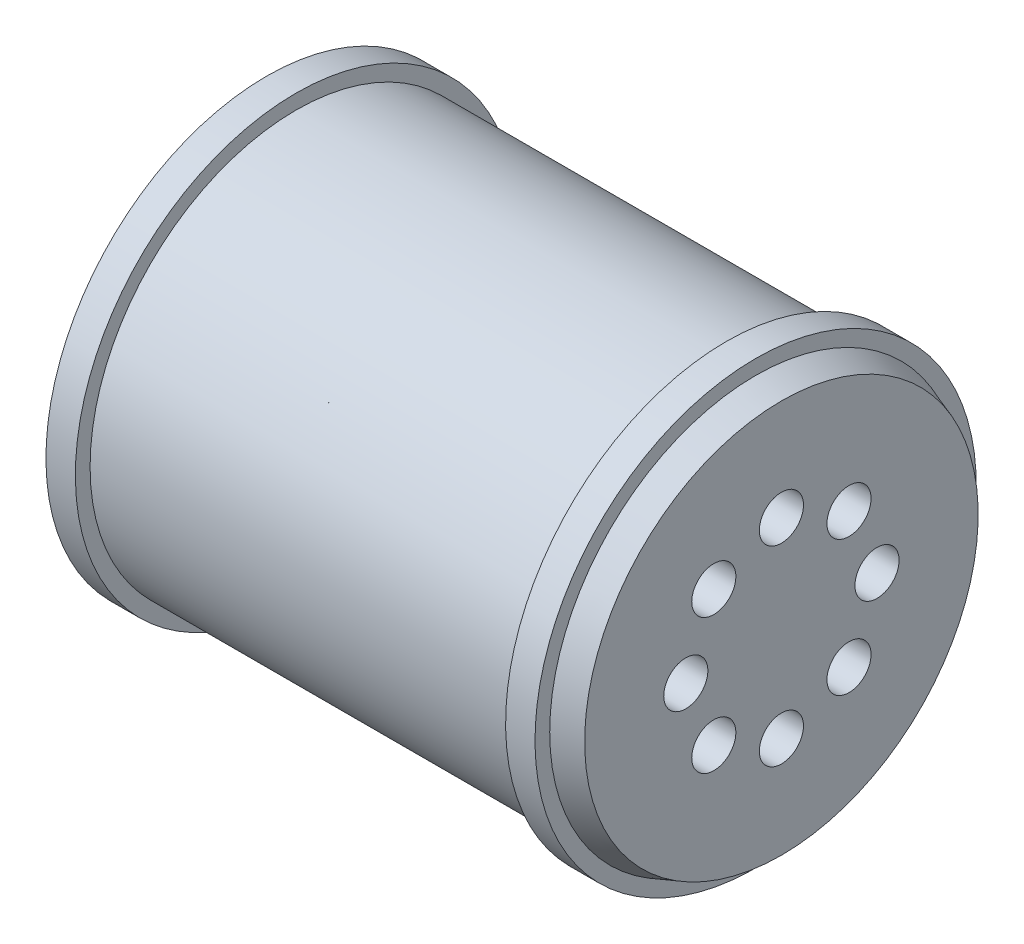
SolidWorks part; units mm, degrees
ref_plane "Front Plane" through (0, 0, 0) normal (0, 0, 1) x (1, 0, 0)
ref_plane "Top Plane" through (0, 0, 0) normal (0, 1, 0) x (1, 0, 0)
ref_plane "Right Plane" through (0, 0, 0) normal (1, 0, 0) x (0, 0, -1)
sketch "Sketch2" plane through (0, 0, 0) normal (0, 0, 1) x (1, 0, 0)
  line L0 (18.248, 0) -> (-8.752, 0)
  line L1 (-8.752, 0) -> (-8.752, 8.5)
  line L2 (-8.752, 8.5) -> (-16.752, 8.5)
  line L3 (-16.752, 8.5) -> (-16.752, 15)
  line L4 (-16.752, 15) -> (-14.752, 15)
  line L5 (-14.752, 15) -> (-14.752, 14)
  line L6 (-14.752, 14) -> (14.4963, 14)
  line L7 (14.4963, 14) -> (14.4963, 15)
  line L8 (14.4963, 15) -> (16.4963, 15)
  line L9 (16.4963, 15) -> (16.4963, 14)
  line L10 (16.4963, 14) -> (18.248, 13.3764)
  line L11 (18.248, 13.3764) -> (18.248, 0)
  point P3 (0, 0)
  point P14 (16.4963, 14)
  point P15 (18.248, 13.3764)
  dimension "D1" = 15
  dimension "D2" = 2
  dimension "D3" = 1
  dimension "D4" = 6.5
  dimension "D5" = 8
  dimension "D6" = 35
revolve "Revolve1" add sketch "Sketch2" angle 360 about L0
sketch "Sketch3" plane through (-8.752, 0, 0) normal (-1, 0, 0) x (0, 0, 1)
  circle A1 centre (0, 6.5) radius 1.5
  circle A2 centre (4.5962, 4.5962) radius 1.5
  circle A3 centre (6.5, 0) radius 1.5
  circle A4 centre (4.5962, -4.5962) radius 1.5
  circle A5 centre (0, -6.5) radius 1.5
  circle A6 centre (-4.5962, -4.5962) radius 1.5
  circle A7 centre (-6.5, 0) radius 1.5
  circle A8 centre (-4.5962, 4.5962) radius 1.5
  point P19 (0, 0)
  dimension "D2" = 3
extrude "Cut-Extrude1" cut sketch "Sketch3" against normal blind 32
sketch "Sketch4" plane through (-8.752, 0, 0) normal (-1, 0, 0) x (0, 0, 1)
  line L0 (0.8292, 1.25) -> (0.8292, -1.25)
  arc A0 (0.8292, 1.25) -> (0.8292, -1.25) centre (0, 0) ccw
  dimension "D1" = 3
  dimension "D2" = 2.5
extrude "Cut-Extrude2" cut sketch "Sketch4" against normal blind 10
